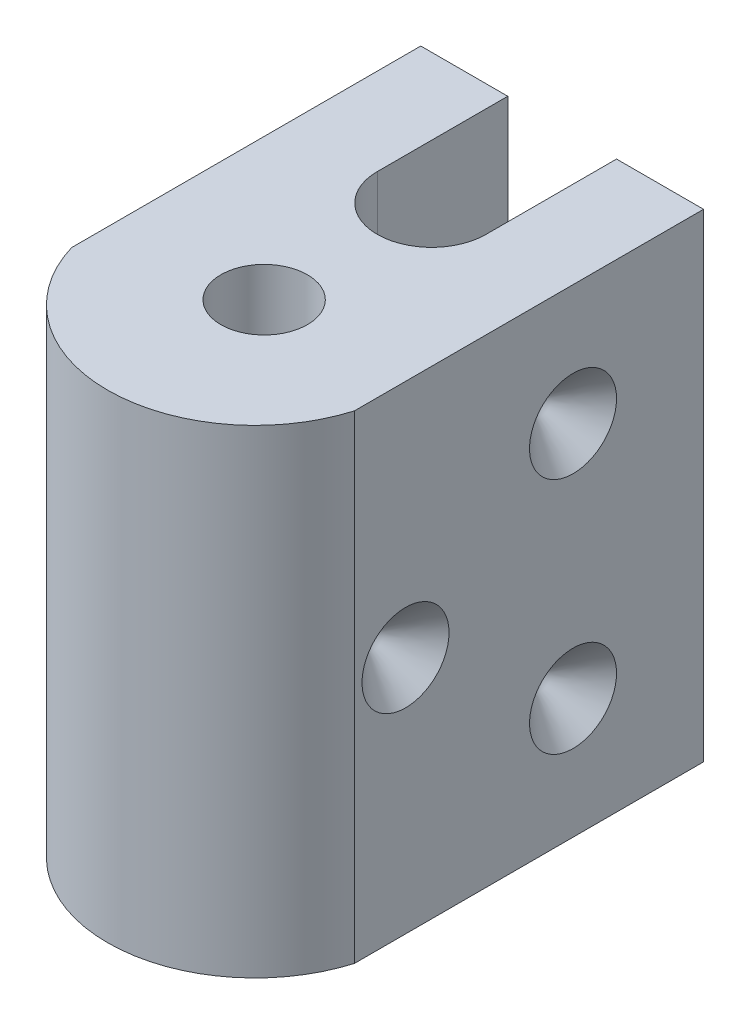
SolidWorks part; units mm, degrees
ref_plane "Front Plane" through (0, 0, 0) normal (0, 0, 1) x (1, 0, 0)
ref_plane "Top Plane" through (0, 0, 0) normal (0, 1, 0) x (1, 0, 0)
ref_plane "Right Plane" through (0, 0, 0) normal (1, 0, 0) x (0, 0, -1)
sketch "Sketch1" plane through (0, 0, 0) normal (0, 1, 0) x (1, 0, 0)
  line L0 (-18.607, 0.4972) -> (-18.607, 5.4972)
  line L1 (-21.107, -13.1379) -> (-21.107, 15.2977) construction
  line L2 (-18.607, 5.4972) -> (-14.607, 5.4972)
  line L3 (-14.607, 5.4972) -> (-14.607, -9.5554)
  line L4 (-27.607, 5.4972) -> (-27.607, -9.5554)
  line L5 (-23.607, 5.4972) -> (-27.607, 5.4972)
  line L6 (-23.607, 0.4972) -> (-23.607, 5.4972)
  circle A0 centre (-21.107, -7.2028) radius 1.9897
  arc A1 (-23.607, 0.4972) -> (-18.607, 0.4972) centre (-21.107, 0.4972) ccw
  arc A2 (-14.607, -9.5554) -> (-27.607, -9.5554) centre (-21.107, -7.6202) cw
  point P2 (-21.107, -2.0028)
  point P3 (-21.107, 0.4972)
  point P4 (-23.607, 0.4972)
  dimension "D1" = 5.2
  dimension "D2" = 2.5
  dimension "D3" = 2.5
  dimension "D4" = 5
  dimension "D5" = 4
  dimension "D6" = 12.7
  dimension "D7" = 5
extrude "Boss-Extrude2" add sketch "Sketch1" along normal blind 22
sketch "Sketch7" plane through (-14.607, 0, 0) normal (1, 0, 0) x (0, 0, -1)
  line L0 (5.4972, 22) -> (5.4972, 0) construction
  line L1 (5.4972, 11) -> (-14.4021, 11) construction
  line L2 (-14.4021, 22) -> (-14.4021, 0) construction
  line L3 (0.4972, 11) -> (0.4972, 22)
  line L4 (-9.5554, 22) -> (5.4972, 22) construction
  circle A0 centre (-7.2028, 11) radius 2
  circle A2 centre (0.4972, 16.47) radius 2
  circle A3 centre (0.4972, 16.47) radius 5.0053
  circle A4 centre (0.4972, 5.53) radius 2
  point P6 (-7.2028, 11)
  point P9 (0.4972, 11)
  dimension "D2" = 5
  dimension "D1" = 12.7
sketch "Sketch8" plane through (0, 0, -5.4972) normal (0, 0, -1) x (-1, 0, 0)
  line L1 (14.607, 22) -> (18.607, 22)
  line L2 (14.607, 22) -> (14.607, 0)
  line L3 (14.607, 0) -> (18.607, 0)
  line L4 (18.607, 22) -> (18.607, 0)
  line L5 (23.607, 22) -> (27.607, 22)
  line L6 (23.607, 22) -> (23.607, 0)
  line L7 (23.607, 0) -> (27.607, 0)
  line L8 (27.607, 22) -> (27.607, 0)
extrude "Boss-Extrude4" add sketch "Sketch8" along normal blind 1
extrude "Cut-Extrude1" cut sketch "Sketch7" against normal blind 11 draft 45 contours L3 A2 | L3 A2 | A0 L1 | L1 A0 | A4
